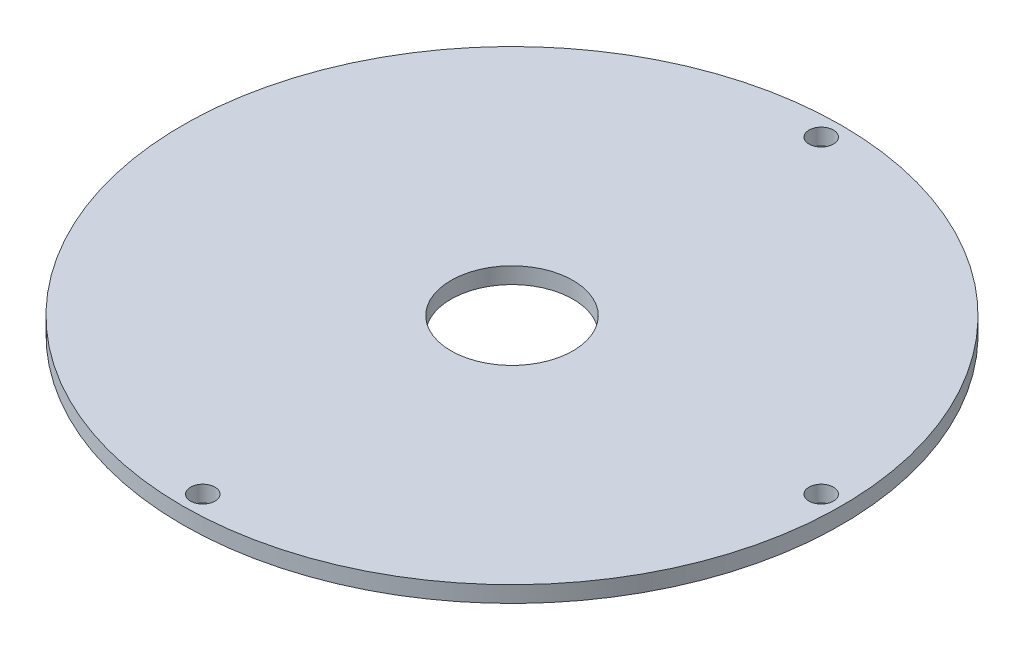
SolidWorks part; units mm, degrees
ref_plane "Front Plane" through (0, 0, 0) normal (0, 0, 1) x (1, 0, 0)
ref_plane "Top Plane" through (0, 0, 0) normal (0, 1, 0) x (1, 0, 0)
ref_plane "Right Plane" through (0, 0, 0) normal (1, 0, 0) x (0, 0, -1)
sketch "Sketch1" plane through (0, 0, 0) normal (0, 1, 0) x (1, 0, 0)
  circle A0 centre (0, 0) radius 40.5
  dimension "D1" = 81
extrude "Boss-Extrude1" add sketch "Sketch1" along normal blind 2
sketch "Sketch2" plane through (0, 2, 0) normal (0, 1, 0) x (1, 0, 0)
  line L0 (0, 31.5738) -> (0, 44.4262) construction
  line L1 (6.9643, 0) -> (69.0357, 0) construction
  line L2 (0, -31.5738) -> (0, -44.4262) construction
  line L3 (38, 0) -> (0, 0) construction
  line L4 (0, 0) -> (0, 31.5738) construction
  line L5 (0, 0) -> (0, -38) construction
  circle A0 centre (0, 38) radius 1.5
  circle A1 centre (38, 0) radius 1.5
  circle A2 centre (0, -38) radius 1.5
  dimension "D1" = 3
  dimension "D4" = 38
  dimension "D2" = 38
  dimension "D3" = 76
extrude "Cut-Extrude1" cut sketch "Sketch2" against normal blind 2
sketch "Sketch3" plane through (0, 2, 0) normal (0, 1, 0) x (1, 0, 0)
  circle A0 centre (0, 0) radius 7.5
  dimension "D1" = 15
extrude "Cut-Extrude2" cut sketch "Sketch3" against normal blind 2
